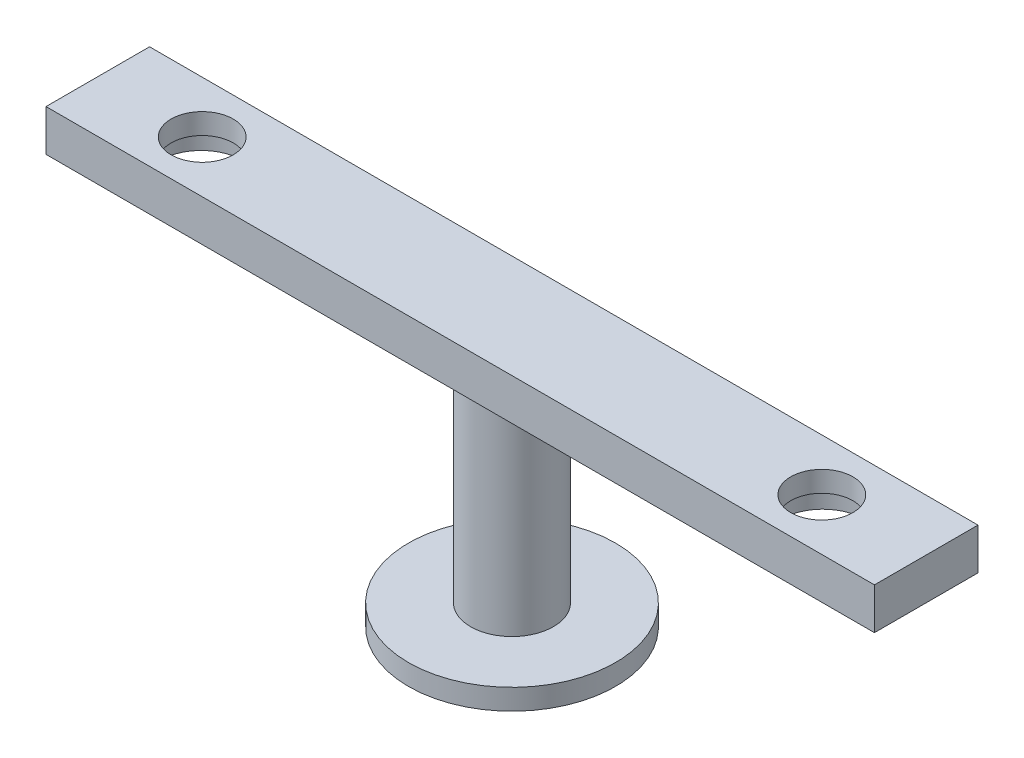
SolidWorks part; units mm, degrees
ref_plane "Front Plane" through (0, 0, 0) normal (1, 0, 0) x (0, 1, 0)
ref_plane "Top Plane" through (0, 0, 0) normal (0, 0, 1) x (0, 1, 0)
ref_plane "Right Plane" through (0, 0, 0) normal (0, 1, 0) x (-1, 0, 0)
sketch "Sketch2" plane through (0, 0, 0) normal (0, 1, 0) x (-1, 0, 0)
  circle A0 centre (0, 0) radius 5
  dimension "D1" = 10
extrude "Boss-Extrude1" add sketch "Sketch2" along normal blind 1
sketch "Sketch3" plane through (0, 0, 0) normal (0, -1, 0) x (1, 0, 0)
  circle A0 centre (0, 0) radius 2.5
  circle A1 centre (0, 0) radius 1.75
  dimension "D1" = 5
  dimension "D2" = 3.5
extrude "Boss-Extrude2" add sketch "Sketch3" along normal blind 0.5
sketch "Sketch4" plane through (0, 1, 0) normal (0, 1, 0) x (-1, 0, 0)
  circle A0 centre (0, 0) radius 2
  dimension "D1" = 4
extrude "Boss-Extrude3" add sketch "Sketch4" along normal blind 10
sketch "Sketch6" plane through (0, 11, 0) normal (0, 1, 0) x (-1, 0, 0)
  line L0 (-20, 2.5) -> (20, 2.5)
  line L1 (-20, -2.5) -> (20, -2.5)
  line L2 (20, -2.5) -> (20, 2.5)
  line L3 (-20, 2.5) -> (-20, -2.5)
  line L4 (-20, 0) -> (20, 0) construction
  line L5 (-2, 0) -> (2, 0) construction
  circle A0 centre (0, 0) radius 2 construction
  dimension "D1" = 20
  dimension "D2" = 40
  dimension "D3" = 5
extrude "Boss-Extrude4" add sketch "Sketch6" along normal blind 2
sketch "Sketch9" plane through (0, 11, 0) normal (0, -1, 0) x (1, 0, 0)
  line L0 (0, -4.753) -> (0, 7.4024) construction
  circle A0 centre (-15, 0) radius 2
  circle A1 centre (15, 0) radius 2
  dimension "D1" = 4
  dimension "D2" = 30
extrude "Cut-Extrude1" cut sketch "Sketch9" against normal blind 1
sketch "Sketch10" plane through (0, 12, 0) normal (0, -1, 0) x (1, 0, 0)
  line L0 (0, -5) -> (0, 5) construction
  circle A0 centre (-14.9596, 0) radius 1.5
  circle A1 centre (0, 0) radius 5 construction
  circle A2 centre (14.9596, 0) radius 1.5
  dimension "D1" = 3
extrude "Cut-Extrude2" cut sketch "Sketch10" against normal blind 31
